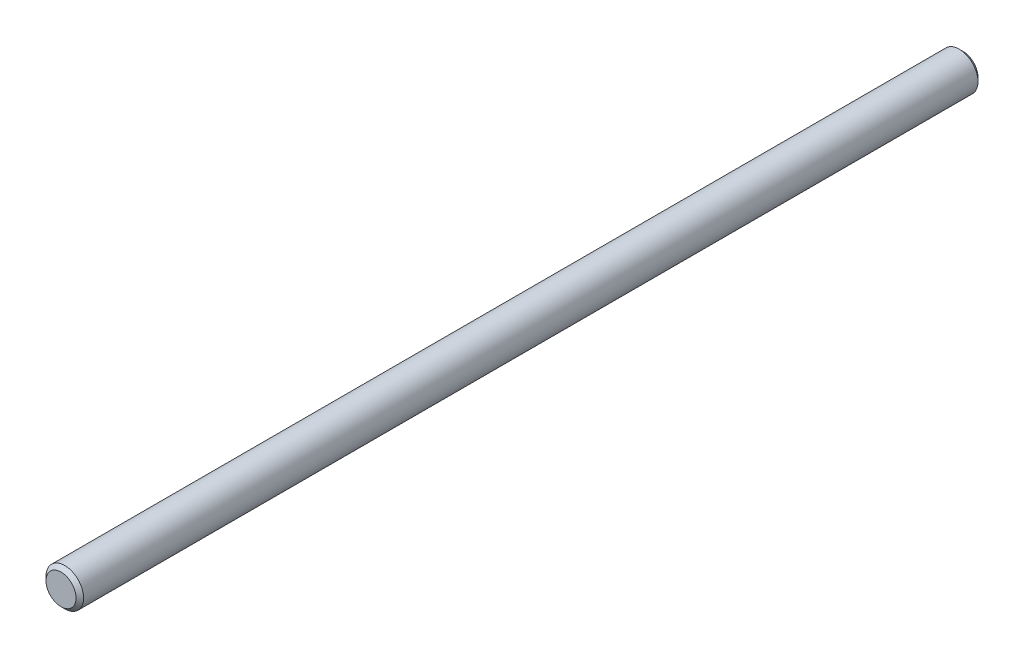
SolidWorks part; units mm, degrees
ref_plane "Front" through (0, 0, 0) normal (0, 0, 1) x (1, 0, 0)
ref_plane "Top" through (0, 0, 0) normal (0, 1, 0) x (1, 0, 0)
ref_plane "Right" through (0, 0, 0) normal (1, 0, 0) x (0, 0, -1)
sketch "Sketch1" plane through (0, 0, 0) normal (0, 0, 1) x (1, 0, 0)
  circle A0 centre (0, 0) radius 6.35
  dimension "Diameter" = 12.7
sketch "Sketch2" plane through (0, 0, 0) normal (1, 0, 0) x (0, 0, -1)
  line L0 (-152.4, 0) -> (152.4, 0) construction
  line L1 (-101.6, 6.35) -> (-101.6, -6.35) construction
  line L2 (17.4625, 0) -> (-17.4625, 0) construction
  line L3 (101.6, 6.35) -> (101.6, -6.35) construction
  line L4 (-152.4, 6.35) -> (-152.4, -6.35) construction
  line L5 (152.4, 6.35) -> (152.4, -6.35) construction
  point P3 (-101.6, 0)
  point P8 (0, 0)
  point P9 (101.6, 0)
  point P15 (-152.4, 0)
  point P18 (152.4, 0)
  dimension "D1" = 12.7
  dimension "Length" = 304.8
  dimension "D2" = 50.8
  dimension "D3" = 50.8
sketch "Sketch3" plane through (0, 0, 0) normal (0, 0, 1) x (1, 0, 0)
  circle A0 centre (0, 0) radius 6.35
  dimension "D1" = 12.7
extrude "Boss-Extrude1" add sketch "Sketch3" along normal mid plane 304.8
chamfer "Chamfer1" distance 1.27 angle 45 2 edges at (6.35, 0, -152.4) (6.35, 0, 152.4)
equation "\"D1@Sketch3\" = \"Diameter@Sketch1\""
equation "\"D1@Boss-Extrude1\" = \"Length@Sketch2\""
equation "\"D1@Chamfer1\" = \"Diameter@Sketch1\" * .1"
equation "\"D1@Sketch2\" = \"Diameter@Sketch1\""
